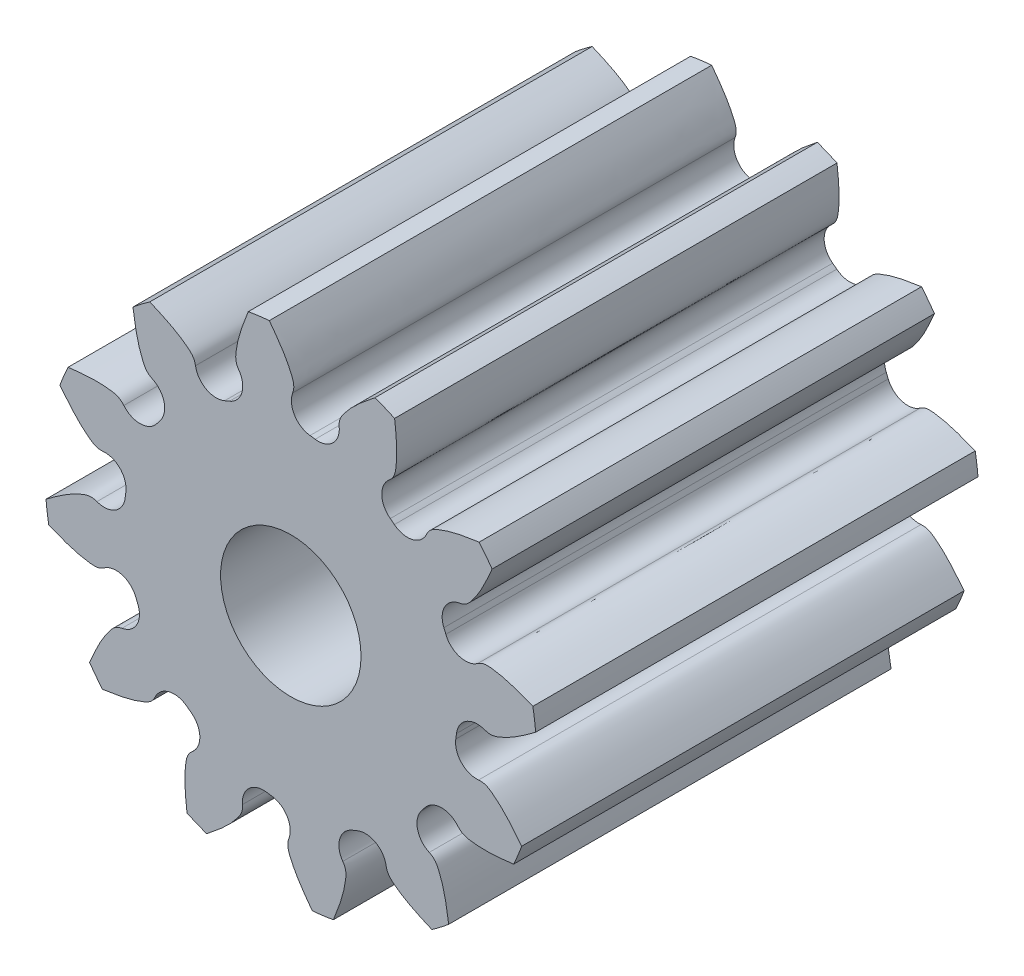
SolidWorks part; units mm, degrees
ref_plane "Plan1" through (0, 0, 0) normal (0, 0, 1) x (1, 0, 0)
ref_plane "Plan2" through (0, 0, 0) normal (0, 1, 0) x (1, 0, 0)
ref_plane "Plan3" through (0, 0, 0) normal (1, 0, 0) x (0, 0, -1)
sketch "Esquisse1" plane through (0, 0, 0) normal (0, 0, 1) x (1, 0, 0)
  circle A0 centre (0, 0) radius 2.375
  dimension "Dp" = 4.75
sketch "Esquisse2" plane through (0, 0, 0) normal (0, 0, 1) x (1, 0, 0)
  line L0 (0, 0) -> (3.4701, 0.4566) construction
  line L1 (2.8489, -0.0425) -> (2.8551, 0.3757) construction
  line L2 (0, 0) -> (2.8489, -0.0425) construction
  line L3 (0, 0) -> (3, 0) construction
  line L4 (0, 0) -> (3.4866, 0.3062) construction
  line L5 (3, 0) -> (3.4866, 0.3062) construction
  line L6 (2.6991, 0.0045) -> (2.2219, 0.3251) construction
  line L7 (2.3391, 0.4113) -> (2.3659, 0.2078)
  circle A0 centre (0, 0) radius 2.8492 construction
  circle A1 centre (0, 0) radius 3 construction
  circle A2 centre (0, 0) radius 3.5 construction
  arc A3 (3.4866, 0.3062) -> (3.4471, 0.6062) centre (0, 0) ccw
  circle A4 centre (0, 0) radius 2.375 construction
  circle A5 centre (0, 0) radius 2.375 construction
  spline S0 degree 3 poles (2.3659, 0.2078) (2.3977, 0.1947) (2.5641, 0.1262) (2.7525, -0.0956) (3.1406, 0.0491) (3.3344, 0.1931) (3.4866, 0.3062) knots 0 0 0 0 0.081432 0.426433 0.549446 1 1 1 1
  spline S1 degree 3 poles (2.3391, 0.4113) (2.3664, 0.4322) (2.5094, 0.5414) (2.6341, 0.8044) (3.0464, 0.765) (3.2708, 0.676) (3.4471, 0.6062) knots 0 0 0 0 0.081432 0.426433 0.549446 1 1 1 1
  dimension "Db" = 5.6984
  dimension "Dn" = 6
  dimension "Dt" = 7
  dimension "Tn" = 0.854
  dimension "Tt" = 5.873
  dimension "Ts" = 7.496
extrude "Base-Extrusion" add sketch "Esquisse1" along normal blind 6.3
ref_axis "Axe1" through (0, 0, -50) along (0, 0, 1)
ref_plane "Plan median" through (0, 0, 3.15) normal (0, 0, -1) x (-1, 0, 0)
extrude "Boss.-Extru.1" add sketch "Esquisse2" along normal blind 6.3
fillet "Congé1" radius 0.3 4 edges at (2.3659, 0.2078, 3.15) (2.3391, 0.4113, 3.15)
pattern_circular "Répétition circulaire1" count 12 over 360 about axis through (0, 0, -50) along (0, 0, 1) of "Boss.-Extru.1", "Congé1"
sketch "Esquisse3" plane through (0, 0, 0) normal (0, 0, 1) x (1, 0, 0)
  circle A0 centre (0, 0) radius 1
  dimension "D1" = 2
extrude "Enlèv. mat.-Extru.2" cut sketch "Esquisse3" along normal through all
sketch "Esquisse4" plane through (0, 0, 0) normal (0, 0, -1) x (-1, 0, 0)
  circle A0 centre (0, 0) radius 3 construction
  circle A1 centre (0, 0) radius 3
  circle A2 centre (0, 0) radius 1 construction
  circle A3 centre (0, 0) radius 1
extrude "Cylindre primitif" [suppressed] add sketch "Esquisse4" along normal up to surface (5 mm away)
ref_plane "Plan médian dent" through (0, 0, 0) normal (-0.1305, 0.9915, 0) x (-0.9915, -0.1305, 0)
ref_plane "Plan médian creux" through (0, 0, 0) normal (-0.3826, 0.9239, 0) x (-0.9239, -0.3826, 0)
equation "\"D1@Boss.-Extru.1\"=\"D1@Base-Extrusion\""
equation "\"D1@Plan median\"=\"D1@Base-Extrusion\"/2"
equation "\"D1@Plan médian creux\"=180/\"D1@Répétition circulaire1\""
